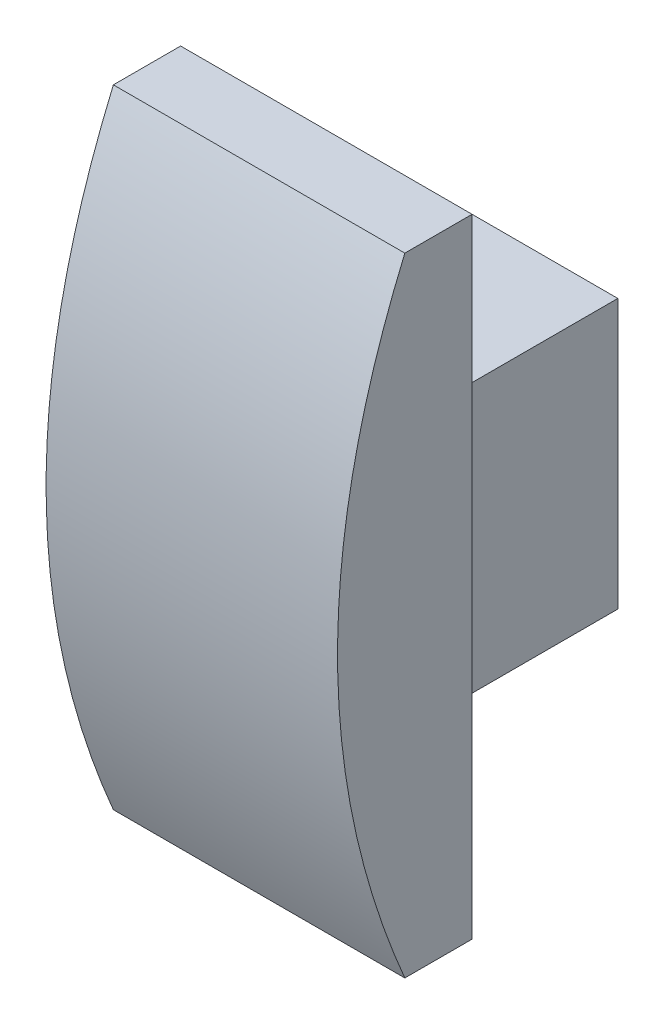
SolidWorks part; units mm, degrees
ref_plane "Płaszczyzna przednia" through (0, 0, 0) normal (0, 0, 1) x (1, 0, 0)
ref_plane "Płaszczyzna górna" through (0, 0, 0) normal (0, 1, 0) x (1, 0, 0)
ref_plane "Płaszczyzna prawa" through (0, 0, 0) normal (1, 0, 0) x (0, 0, -1)
sketch "Szkic1" plane through (0, 0, 0) normal (0, 0, 1) x (1, 0, 0)
  line L0 (0, -1.05) -> (2.1, -1.05) construction
  line L1 (0, 0) -> (2.1, 0)
  line L2 (0, 0) -> (0, -2.1)
  line L3 (0, -2.1) -> (2.1, -2.1)
  line L4 (2.1, 0) -> (2.1, -2.1)
  line L5 (-1.45, 1.95) -> (3.55, 1.95)
  line L6 (-1.45, 1.95) -> (-1.45, -4.05)
  line L7 (-1.45, -4.05) -> (3.55, -4.05)
  line L8 (3.55, 1.95) -> (3.55, -4.05)
  line L9 (1.05, 0) -> (1.05, -2.1) construction
  point P9 (1.05, -4.05)
  dimension "D1" = 2.1
  dimension "D2" = 2.1
  dimension "D3" = 5
  dimension "D4" = 6
extrude "Dodanie-wyciągnięcie1" add sketch "Szkic1" along normal blind 4
sketch "Szkic3" plane through (0, 0, 4) normal (0, 0, 1) x (1, 0, 0)
  line L0 (0, -1.05) -> (2.1, -1.05) construction
  line L1 (-2.2, 5.95) -> (4.3, 5.95)
  line L2 (-2.2, 5.95) -> (-2.2, -8.05)
  line L3 (-2.2, -8.05) -> (4.3, -8.05)
  line L4 (4.3, 5.95) -> (4.3, -8.05)
  line L5 (-1.45, -4.05) -> (3.55, -4.05) construction
  line L7 (1.05, 0) -> (1.05, -2.1) construction
  dimension "D1" = 4
  dimension "D2" = 6.5
extrude "Dodanie-wyciągnięcie2" add sketch "Szkic3" along normal blind 3
sketch "Szkic4" plane through (-2.2, 0, 0) normal (-1, 0, 0) x (0, 0, 1)
  line L2 (7, 5.95) -> (4, 5.95) construction
  line L3 (7, 5.95) -> (7, -8.05) construction
  line L4 (7, -8.05) -> (4, -8.05) construction
  line L5 (5.5, 5.95) -> (7, 5.95)
  line L6 (7, 5.95) -> (7, -8.05)
  line L7 (7, -8.05) -> (5.5, -8.05)
  spline S0 degree 2 poles (5.5, 5.95) (8.5, -1.05) (5.5, -8.05) knots 0 0 0 1 1 1
  line M2 (4, -8.05) -> (7, -8.05)
  line M3 (7, -8.05) -> (7, 5.95)
  line M4 (7, 5.95) -> (4, 5.95)
extrude "Wytnij-wyciągnięcie1" cut sketch "Szkic4" against normal through all contours S0 M3 M2 | S0 L6 M4
